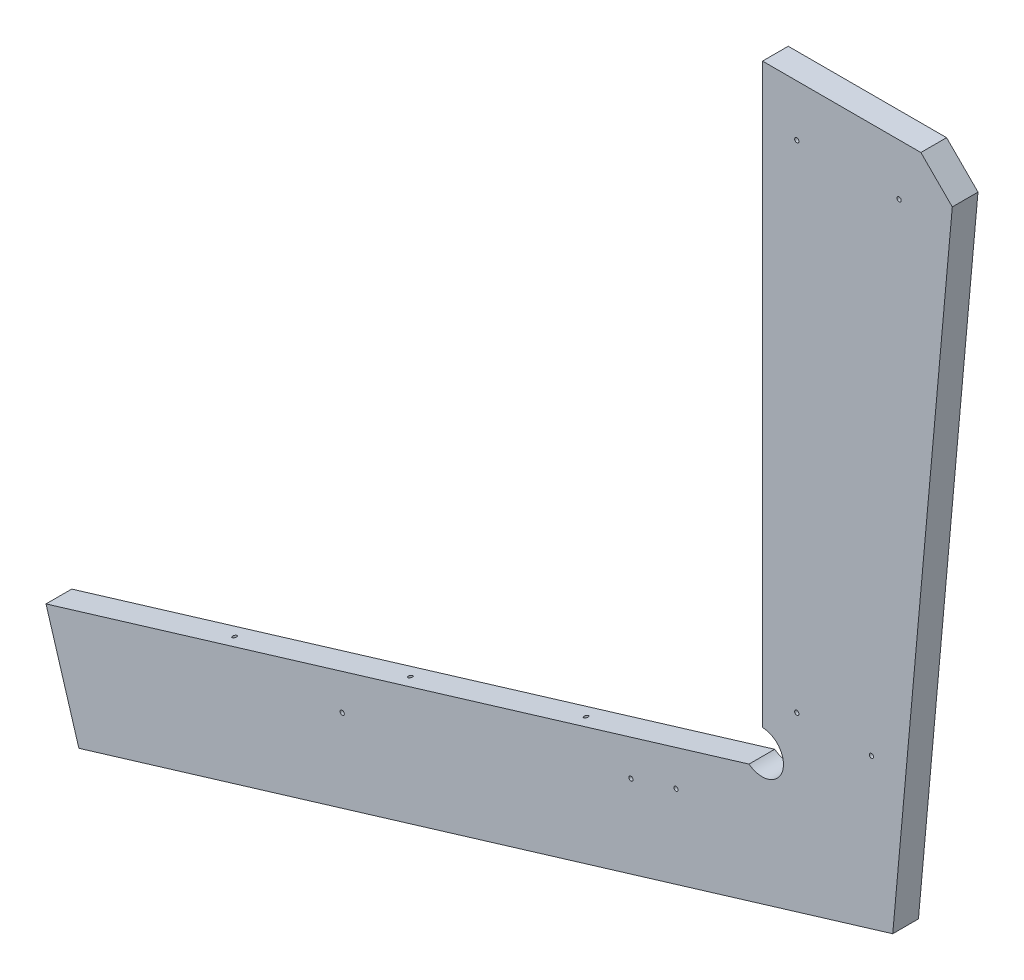
SolidWorks part; units mm, degrees
material "Beech"
ref_plane "Front Plane" through (0, 0, 0) normal (0, 0, 1) x (1, 0, 0)
ref_plane "Top Plane" through (0, 0, 0) normal (0, 1, 0) x (1, 0, 0)
ref_plane "Right Plane" through (0, 0, 0) normal (1, 0, 0) x (0, 0, -1)
sketch "Sketch1" plane through (0, 0, 0) normal (0, 0, 1) x (1, 0, 0)
  line L0 (12.7, 12.7) -> (12.7, -415.1856)
  line L1 (12.7, 12.7) -> (155.4923, 12.7)
  line L2 (155.4923, 12.7) -> (109.2456, -499.298)
  line L3 (-525.0991, -623.2821) -> (-544.935, -557.7423) construction
  line L6 (2.6872, -443.6415) -> (-518.462, -601.37)
  line L7 (55, 0) -> (-55, 0) construction
  line L8 (-518.462, -601.37) -> (-494.089, -681.9004)
  line L9 (-522.1409, -589.2145) -> (-518.462, -601.37) construction
  line L10 (-518.462, -601.37) -> (16.3789, -439.4976) construction
  line L11 (-477.5339, -736.6) -> (103.7007, -560.6863) construction
  line L12 (-494.089, -681.9004) -> (109.2456, -499.298)
  line L13 (-494.089, -681.9004) -> (-477.5339, -736.6) construction
  line L14 (109.2456, -499.298) -> (103.7007, -560.6863) construction
  arc A0 (2.6872, -443.6415) -> (12.7, -415.1856) centre (12.3644, -431.057) ccw
  point P18 (106.9393, -524.8312)
  point P20 (-494.089, -667.7661)
  point P21 (109.2456, -486.8104)
  dimension "D3" = 31.75
  dimension "D1" = 736.6
  dimension "D2" = 112
  dimension "D4" = 129.6293
  dimension "D5" = 91.3362
  dimension "D6" = 57.15
extrude "Boss-Extrude1" add sketch "Sketch1" against normal blind 19.05
ref_plane "CL" through (0, 0, -9.525) normal (0, 0, 1) x (1, 0, 0)
chamfer "Chamfer1" distance 25.4 angle 45 1 edges at (155.4923, 12.7, -9.525)
hole_wizard "Hole1" positions "Sketch2" profile "Sketch3" legacy
sketch "Sketch2" plane through (0, 10.4243, -184.525) normal (-1, 0, 0) x (0, 0, -1)
  line L8 (155.95, -2.2757) -> (155.95, 437.7664) construction
  line L11 (175, -2.2757) -> (175, 437.7664) construction
  line L15 (155.95, -2.2757) -> (155.95, 107.7348)
  line L16 (155.95, 107.7348) -> (155.95, 217.7454)
  line L17 (155.95, 217.7454) -> (155.95, 327.7559)
  line L18 (155.95, 327.7559) -> (155.95, 437.7664)
  line L20 (175, -2.2757) -> (175, 85.7327)
  line L21 (175, 85.7327) -> (175, 173.7411)
  line L22 (175, 173.7411) -> (175, 261.7496)
  line L23 (175, 261.7496) -> (175, 349.758)
  line L24 (175, 349.758) -> (175, 437.7664)
  line L25 (0, 155.0243) -> (0, 437.7664) construction
  point P36 (155.95, 107.7348)
  point P40 (155.95, 327.7559)
  point P46 (175, 85.7327)
  point P52 (175, 349.758)
  point P77 (-175, 349.758)
  point P80 (-175, 85.7327)
  point P81 (-155.95, 327.7559)
  point P83 (-155.95, 107.7348)
sketch "Sketch3" plane through (0, -97.3105, -28.575) normal (0, 1, 0) x (0, 0, 1)
  line L0 (0, 0) -> (0, 32.7039)
  line L1 (0, 32.7039) -> (1.5875, 31.75)
  line L2 (1.5875, 31.75) -> (1.5875, 4.0177)
  line L3 (1.5875, 4.0177) -> (5.08, 0)
  line L4 (5.08, 0) -> (0, 0)
  line L5 (0, -14.3089) -> (0, 102.4216) construction
  line L6 (0, 32.7039) -> (-1.5875, 31.75) construction
  line L7 (-1.5875, 4.0177) -> (-5.08, 0) construction
  dimension "Diameter" = 3.175
  dimension "Depth" = 31.75
  dimension "C-Sink Diameter" = 10.16
  dimension "C-Sink Angle" = 82
  dimension "Drill Angle" = 118
hole_wizard "Hole2" positions "Sketch4" profile "Sketch5" legacy
sketch "Sketch4" plane through (0, 10.4243, 165.475) normal (-1, 0, 0) x (0, 0, -1)
  line L8 (155.95, -2.2757) -> (155.95, 437.7664) construction
  line L11 (175, -2.2757) -> (175, 437.7664) construction
  line L15 (155.95, -2.2757) -> (155.95, 107.7348)
  line L16 (155.95, 107.7348) -> (155.95, 217.7454)
  line L17 (155.95, 217.7454) -> (155.95, 327.7559)
  line L18 (155.95, 327.7559) -> (155.95, 437.7664)
  line L20 (175, -2.2757) -> (175, 85.7327)
  line L21 (175, 85.7327) -> (175, 173.7411)
  line L22 (175, 173.7411) -> (175, 261.7496)
  line L23 (175, 261.7496) -> (175, 349.758)
  line L24 (175, 349.758) -> (175, 437.7664)
  line L25 (0, 155.0243) -> (0, 437.7664) construction
  point P36 (155.95, 107.7348)
  point P40 (155.95, 327.7559)
  point P46 (175, 85.7327)
  point P52 (175, 349.758)
  point P77 (-175, 349.758)
  point P80 (-175, 85.7327)
  point P81 (-155.95, 327.7559)
  point P83 (-155.95, 107.7348)
sketch "Sketch5" plane through (0, -97.3105, 321.425) normal (0, 1, 0) x (0, 0, 1)
  line L0 (0, 0) -> (0, 32.7039)
  line L1 (0, 32.7039) -> (1.5875, 31.75)
  line L2 (1.5875, 31.75) -> (1.5875, 4.0177)
  line L3 (1.5875, 4.0177) -> (5.08, 0)
  line L4 (5.08, 0) -> (0, 0)
  line L5 (0, -14.3089) -> (0, 102.4216) construction
  line L6 (0, 32.7039) -> (-1.5875, 31.75) construction
  line L7 (-1.5875, 4.0177) -> (-5.08, 0) construction
  dimension "Diameter" = 3.175
  dimension "Depth" = 31.75
  dimension "C-Sink Diameter" = 10.16
  dimension "C-Sink Angle" = 82
  dimension "Drill Angle" = 118
hole_wizard "Hole3" positions "Sketch6" profile "Sketch7" legacy
sketch "Sketch6" plane through (264.6961, -351.0742, -184.525) normal (-0.2897, 0.9571, 0) x (0, 0, -1)
  point P49 (175, 685.961)
  point P51 (175, 549.8373)
  point P53 (175, 413.7135)
  point P67 (81.55, 779.6497)
  point P73 (81.55, 652.3446)
  point P79 (62.5, 662.9534)
  point P83 (62.5, 769.041)
  point P103 (-62.5, 769.041)
  point P105 (-62.5, 662.9534)
  point P106 (-81.55, 652.3446)
  point P109 (-81.55, 779.6497)
  point P110 (-175, 413.7135)
  point P111 (-175, 549.8373)
  point P112 (-175, 685.961)
  point P115 (-82.7375, 600.3846)
  point P117 (0, 600.3846)
  point P119 (82.7375, 600.3846)
  point P129 (0, 376.7378)
  point P131 (-82.7375, 376.7378)
  point P133 (82.7375, 376.7378)
sketch "Sketch7" plane through (-391.8536, -549.7824, -359.525) normal (0, 0, 1) x (-0.9571, -0.2897, 0)
  line L0 (0, 0) -> (0, 32.7039)
  line L1 (0, 32.7039) -> (1.5875, 31.75)
  line L2 (1.5875, 31.75) -> (1.5875, 4.0177)
  line L3 (1.5875, 4.0177) -> (5.08, 0)
  line L4 (5.08, 0) -> (0, 0)
  line L5 (0, -14.3089) -> (0, 102.4216) construction
  line L6 (0, 32.7039) -> (-1.5875, 31.75) construction
  line L7 (-1.5875, 4.0177) -> (-5.08, 0) construction
  dimension "Diameter" = 3.175
  dimension "Depth" = 31.75
  dimension "C-Sink Diameter" = 10.16
  dimension "C-Sink Angle" = 82
  dimension "Drill Angle" = 118
hole_wizard "Hole4" positions "Sketch8" profile "Sketch9" legacy
sketch "Sketch8" plane through (264.6961, -351.0742, 165.475) normal (-0.2897, 0.9571, 0) x (0, 0, -1)
  point P49 (175, 685.961)
  point P51 (175, 549.8373)
  point P53 (175, 413.7135)
  point P67 (81.55, 779.6497)
  point P73 (81.55, 652.3446)
  point P79 (62.5, 662.9534)
  point P83 (62.5, 769.041)
  point P103 (-62.5, 769.041)
  point P105 (-62.5, 662.9534)
  point P106 (-81.55, 652.3446)
  point P109 (-81.55, 779.6497)
  point P110 (-175, 413.7135)
  point P111 (-175, 549.8373)
  point P112 (-175, 685.961)
  point P115 (-82.7375, 600.3846)
  point P117 (0, 600.3846)
  point P119 (82.7375, 600.3846)
  point P129 (0, 376.7378)
  point P131 (-82.7375, 376.7378)
  point P133 (82.7375, 376.7378)
sketch "Sketch9" plane through (-391.8536, -549.7824, -9.525) normal (0, 0, 1) x (-0.9571, -0.2897, 0)
  line L0 (0, 0) -> (0, 32.7039)
  line L1 (0, 32.7039) -> (1.5875, 31.75)
  line L2 (1.5875, 31.75) -> (1.5875, 4.0177)
  line L3 (1.5875, 4.0177) -> (5.08, 0)
  line L4 (5.08, 0) -> (0, 0)
  line L5 (0, -14.3089) -> (0, 102.4216) construction
  line L6 (0, 32.7039) -> (-1.5875, 31.75) construction
  line L7 (-1.5875, 4.0177) -> (-5.08, 0) construction
  dimension "Diameter" = 3.175
  dimension "Depth" = 31.75
  dimension "C-Sink Diameter" = 10.16
  dimension "C-Sink Angle" = 82
  dimension "Drill Angle" = 118
hole_wizard "Hole5" positions "Sketch10" profile "Sketch11" legacy
sketch "Sketch10" plane through (155.2867, 10.4243, -19.05) normal (0, 0, -1) x (-0.09, -0.9959, 0)
  line L0 (48.5061, 138.7859) -> (35.9701, 0) construction
  line L5 (414.5728, 105.7206) -> (405.0235, 0) construction
  line L7 (490.0108, 170.6797) -> (621.0107, 117.7523) construction
  line L12 (503.094, 203.0616) -> (634.0938, 150.1342) construction
  line L16 (586.8736, 410.4234) -> (717.8734, 357.496) construction
  line L19 (597.4602, 127.2674) -> (610.5433, 159.6493) construction
  line L20 (610.5433, 159.6493) -> (694.3229, 367.011) construction
  line L22 (513.5613, 161.1647) -> (526.6445, 193.5466) construction
  line L23 (526.6445, 193.5466) -> (610.424, 400.9084) construction
  point P0 (46.2211, 113.4889)
  point P2 (39.3976, 37.9455)
  point P4 (412.2879, 80.4236)
  point P51 (407.3085, 25.297)
  point P56 (513.5613, 161.1647)
  point P58 (597.4602, 127.2674)
  point P61 (610.5433, 159.6493)
  point P63 (694.3229, 367.011)
  point P66 (526.6445, 193.5466)
  point P68 (610.424, 400.9084)
sketch "Sketch11" plane through (38.1, -25.4, -19.05) normal (1, 0, 0) x (0, 1, 0)
  line L0 (0, 0) -> (0, 39.0539)
  line L1 (0, 39.0539) -> (1.5875, 38.1)
  line L2 (1.5875, 38.1) -> (1.5875, 4.0177)
  line L3 (1.5875, 4.0177) -> (5.08, 0)
  line L4 (5.08, 0) -> (0, 0)
  line L5 (0, -14.3089) -> (0, 102.4216) construction
  line L6 (0, 39.0539) -> (-1.5875, 38.1) construction
  line L7 (-1.5875, 4.0177) -> (-5.08, 0) construction
  dimension "Diameter" = 3.175
  dimension "Depth" = 38.1
  dimension "C-Sink Diameter" = 10.16
  dimension "C-Sink Angle" = 82
  dimension "Drill Angle" = 118
hole_wizard "Hole6" positions "Sketch12" profile "Sketch13" legacy
sketch "Sketch12" plane through (-643.7058, -231.395, 165.475) normal (-0.9571, -0.2897, 0) x (0, 0, -1)
  line L0 (207.775, 377.6924) -> (207.775, 288.0915) construction
  line L4 (108.65, 377.6924) -> (108.65, 288.0915) construction
  line L8 (175, 506.2803) -> (175, 390.3924) construction
  line L12 (94.25, 390.3924) -> (94.25, 377.6924) construction
  line L17 (94.25, 384.0424) -> (217.3, 384.0424) construction
  line L19 (94.25, 384.0424) -> (135.2667, 384.0424)
  line L20 (135.2667, 384.0424) -> (176.2833, 384.0424)
  line L21 (176.2833, 384.0424) -> (217.3, 384.0424)
  line L22 (0, 288.0915) -> (0, 390.3924) construction
  point P39 (108.65, 332.8919)
  point P41 (207.775, 332.8919)
  point P43 (175, 448.3363)
  point P47 (135.2667, 384.0424)
  point P49 (176.2833, 384.0424)
  point P65 (-175, 448.3363)
  point P66 (-135.2667, 384.0424)
  point P67 (-176.2833, 384.0424)
  point P68 (-207.775, 332.8919)
  point P69 (-108.65, 332.8919)
sketch "Sketch13" plane through (-547.2741, -550.0138, 274.125) normal (0, 0, 1) x (0.2897, -0.9571, 0)
  line L0 (0, 0) -> (0, 39.0539)
  line L1 (0, 39.0539) -> (1.5875, 38.1)
  line L2 (1.5875, 38.1) -> (1.5875, 4.0177)
  line L3 (1.5875, 4.0177) -> (5.08, 0)
  line L4 (5.08, 0) -> (0, 0)
  line L5 (0, -14.3089) -> (0, 102.4216) construction
  line L6 (0, 39.0539) -> (-1.5875, 38.1) construction
  line L7 (-1.5875, 4.0177) -> (-5.08, 0) construction
  dimension "Diameter" = 3.175
  dimension "Depth" = 38.1
  dimension "C-Sink Diameter" = 10.16
  dimension "C-Sink Angle" = 82
  dimension "Drill Angle" = 118
